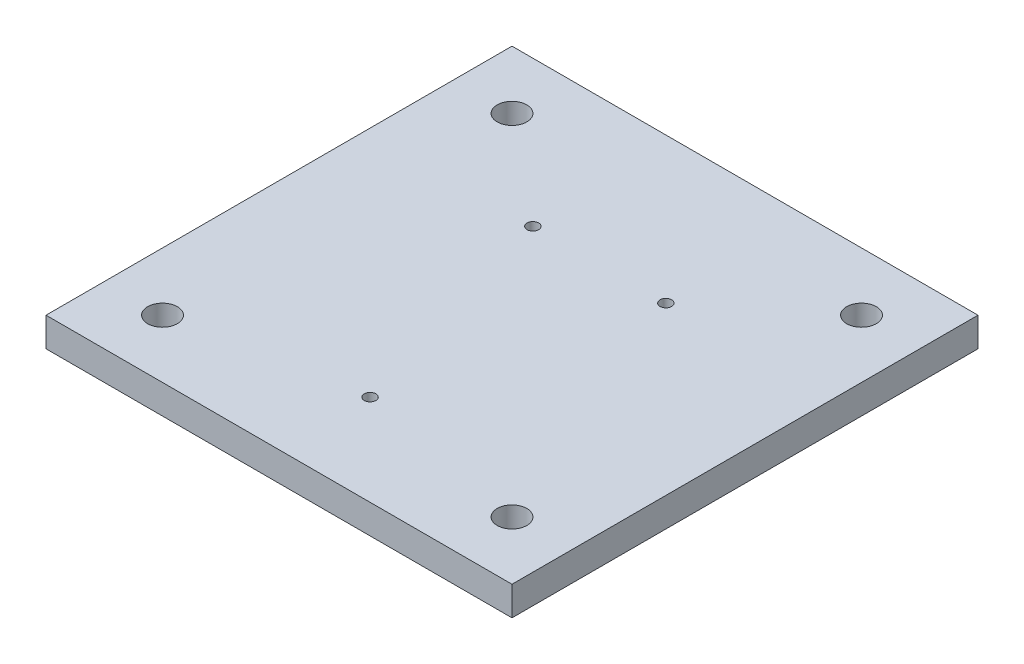
SolidWorks part; units mm, degrees
material "Brass"
ref_plane "Front Plane" through (0, 0, 0) normal (0, 0, 1) x (1, 0, 0)
ref_plane "Top Plane" through (0, 0, 0) normal (0, 1, 0) x (1, 0, 0)
ref_plane "Right Plane" through (0, 0, 0) normal (1, 0, 0) x (0, 0, -1)
sketch "Sketch1" plane through (0, 0, 0) normal (0, 1, 0) x (1, 0, 0)
  line L0 (0, 50.8) -> (0, -50.8) construction
  line L1 (50.8, -50.8) -> (-50.8, -50.8)
  line L2 (50.8, -50.8) -> (50.8, 50.8)
  line L3 (50.8, 50.8) -> (-50.8, 50.8)
  line L4 (-50.8, -50.8) -> (-50.8, 50.8)
  circle A0 centre (-14.5, 19.05) radius 1.27
  circle A1 centre (14.5, 19.05) radius 1.27
  circle A2 centre (0, -30.95) radius 1.27
  circle A3 centre (-38.1, 38.1) radius 3.2281
  circle A4 centre (38.1, 38.1) radius 3.2281
  circle A10 centre (38.1, -38.1) radius 3.2281
  circle A18 centre (-38.1, -38.1) radius 3.2281
  circle A61 centre (-38.1, -63.5) radius 3.2281 [skipped]
  circle A62 centre (38.1, -63.5) radius 3.2281 [skipped]
  circle A63 centre (-38.1, 12.7) radius 3.2281 [skipped]
  circle A64 centre (-38.1, 0) radius 3.2281 [skipped]
  circle A65 centre (-38.1, -12.7) radius 3.2281 [skipped]
  circle A66 centre (-38.1, -25.4) radius 3.2281 [skipped]
  circle A67 centre (38.1, 12.7) radius 3.2281 [skipped]
  circle A68 centre (38.1, 0) radius 3.2281 [skipped]
  circle A69 centre (38.1, -12.7) radius 3.2281 [skipped]
  circle A70 centre (38.1, -25.4) radius 3.2281 [skipped]
  circle A71 centre (-38.1, -50.8) radius 3.2281 [skipped]
  circle A72 centre (-38.1, 25.4) radius 3.2281 [skipped]
  circle A73 centre (38.1, 25.4) radius 3.2281 [skipped]
  circle A74 centre (38.1, -50.8) radius 3.2281 [skipped]
  point P0 (0, 0)
  point P14 (0, 0)
  point P17 (0, 0)
  point P50 (0, 0)
  dimension "D1" = 2.54
  dimension "D11" = 76.2
  dimension "D2" = 101.6
  dimension "D3" = 101.6
  dimension "D4" = 50
  dimension "D5" = 29
  dimension "D6" = 12.7
  dimension "D7" = 38.1
  dimension "D10" = 31.75
  dimension "D13" = 76.2
  dimension "D8" = 2
  dimension "D9" = 9
extrude "Boss-Extrude1" add sketch "Sketch1" along normal blind 6.35
